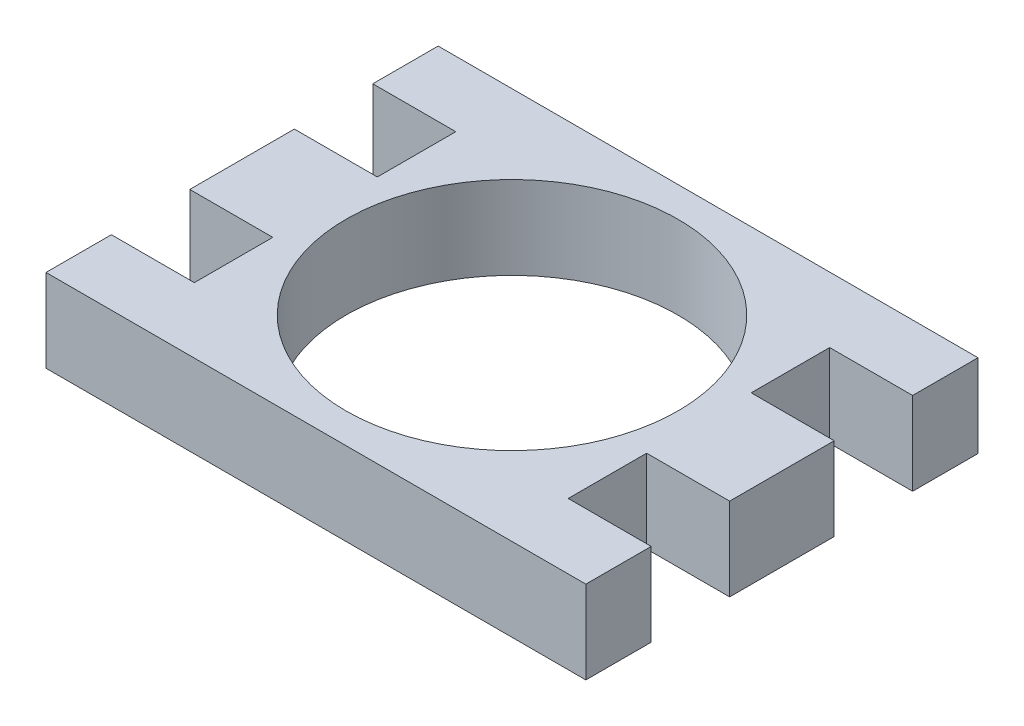
SolidWorks part; units mm, degrees
ref_plane "Front Plane" through (0, 0, 0) normal (0, 0, 1) x (1, 0, 0)
ref_plane "Top Plane" through (0, 0, 0) normal (0, 1, 0) x (1, 0, 0)
ref_plane "Right Plane" through (0, 0, 0) normal (1, 0, 0) x (0, 0, -1)
sketch "Sketch1" plane through (0, 0, 0) normal (0, 1, 0) x (1, 0, 0)
  line L0 (-20.65, 0) -> (0, 0) construction
  line L1 (-20.65, 15) -> (20.65, 15)
  line L2 (-20.65, 15) -> (-20.65, 10)
  line L3 (-20.65, -15) -> (20.65, -15)
  line L5 (0, 15) -> (0, -15) construction
  line L6 (20.65, -10) -> (20.65, -15)
  line L7 (20.65, -10) -> (14.3, -10)
  line L8 (-20.65, -10) -> (-14.3, -10)
  line L9 (-14.3, -10) -> (-14.3, -4)
  line L10 (-14.3, -4) -> (-20.65, -4)
  line L11 (-20.65, 4) -> (-20.65, -4)
  line L12 (-20.65, -10) -> (-20.65, -15)
  line L13 (-20.65, 10) -> (-14.3, 10)
  line L14 (-14.3, 10) -> (-14.3, 4)
  line L15 (-14.3, 4) -> (-20.65, 4)
  line L16 (14.3, -10) -> (14.3, -4)
  line L17 (14.3, -4) -> (20.65, -4)
  line L18 (20.65, 4) -> (20.65, -4)
  line L19 (14.3, 4) -> (20.65, 4)
  line L20 (14.3, 10) -> (14.3, 4)
  line L21 (20.65, 10) -> (14.3, 10)
  line L22 (20.65, 15) -> (20.65, 10)
  circle A0 centre (0, 0) radius 12.7
  dimension "D1" = 25.4
  dimension "D2" = 6.35
  dimension "D3" = 8
  dimension "D4" = 6
  dimension "D5" = 20.65
  dimension "D6" = 30
extrude "Boss-Extrude1" add sketch "Sketch1" along normal blind 6.35
